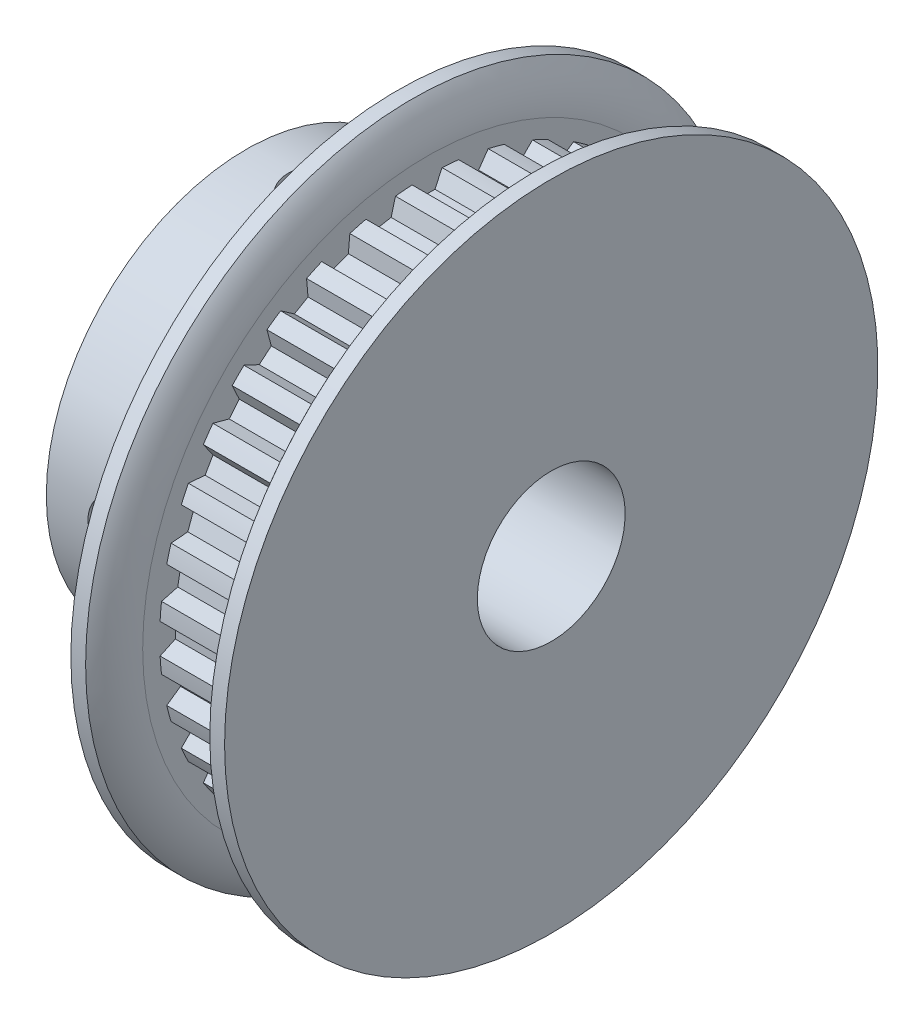
SolidWorks part; units mm, degrees
ref_plane "Front Plane" through (0, 0, 0) normal (0, 0, 1) x (1, 0, 0)
ref_plane "Top Plane" through (0, 0, 0) normal (0, 1, 0) x (1, 0, 0)
ref_plane "Right Plane" through (0, 0, 0) normal (1, 0, 0) x (0, 0, -1)
sketch "Sketch2" plane through (0, 0, 0) normal (1, 0, 0) x (0, 0, -1)
  line L3 (0, 0) -> (0, 10.8204) construction
  line L6 (0, -11.3284) -> (0, -11.6459) construction
  line L7 (-0.5715, 11.314) -> (-0.3389, 10.8151)
  line L8 (0.5715, 11.314) -> (0.3389, 10.8151)
  line L9 (-0.5715, 11.314) -> (-0.6438, 11.4691)
  line L10 (0.5715, 11.314) -> (0.6438, 11.4691)
  line L12 (-0.3389, 10.8151) -> (0.3389, 10.8151)
  line L14 (0, 11.3284) -> (0, 11.6459) construction
  line L15 (0, 0) -> (0, -1.143) construction
  circle A0 centre (0, 0) radius 11.6459 construction
  circle A1 centre (0, 0) radius 10.8204 construction
  circle A2 centre (0, 0) radius 11.3284 construction
  arc A7 (0.6438, 11.4691) -> (-0.6438, 11.4691) centre (0, 0) ccw
  point P5 (0, 11.4872)
  dimension "D3" = 0.3175
  dimension "D1" = 50
sketch "Sketch1" plane through (0, 0, 0) normal (0, 0, 1) x (1, 0, 0)
  line L0 (-6.5532, 0) -> (6.5532, 0) construction
  line L1 (-6.5532, 3.175) -> (6.5532, 3.175)
  line L2 (-6.5532, 3.175) -> (-6.5532, 8.5852)
  line L3 (-0.0508, 14.0335) -> (0.5842, 14.0335)
  line L4 (1.2192, 11.6459) -> (1.2192, 12.2174)
  line L5 (1.2192, 12.7889) -> (1.2192, 11.6459) construction
  line L6 (1.2192, 11.6459) -> (5.2832, 11.6459)
  line L7 (5.2832, 11.6459) -> (5.2832, 12.2174)
  line L8 (5.2832, 11.6459) -> (6.5532, 11.6459) construction
  line L9 (5.9182, 14.0335) -> (6.5532, 14.0335)
  line L10 (6.5532, 14.0335) -> (6.5532, 3.175)
  line L11 (5.9182, 11.6459) -> (5.9182, 14.0335) construction
  line L12 (-3.302, 8.5852) -> (-3.302, 3.175) construction
  line L13 (-0.0508, 14.0335) -> (-0.0508, 8.5852)
  line L14 (-0.0508, 8.5852) -> (-6.5532, 8.5852)
  arc A0 (5.2832, 12.2174) -> (5.9182, 14.0335) centre (8.1977, 12.2174) cw
  arc A1 (1.2192, 12.2174) -> (0.5842, 14.0335) centre (-1.6953, 12.2174) ccw
  dimension "Bore Size" = 6.35
  dimension "Overall Width" = 13.1064
  dimension "Inside Width" = 4.064
  dimension "OD" = 28.067
  dimension "D2" = 23.2918
  dimension "D3" = 1.143
  dimension "D4" = 0.5715
  dimension "Outside Width" = 6.604
revolve "Revolve1" add sketch "Sketch1" angle 360 mid plane about L0
sketch "Sketch4" plane through (1.2192, 0, 0) normal (1, 0, 0) x (0, 0, -1)
  circle A0 centre (0, 0) radius 11.4872
  circle A2 centre (0, 0) radius 11.6459
  circle A3 centre (0, 0) radius 11.6459 construction
extrude "Cut-Extrude2" cut sketch "Sketch4" along normal up to surface (4.064 mm away) up to face at (5.2832, 0, 11.6459)
sketch "Sketch3" plane through (1.2192, 0, 0) normal (1, 0, 0) x (0, 0, -1)
  line L2 (-0.5715, 11.314) -> (-0.3389, 10.8151) construction
  line L3 (-0.3389, 10.8151) -> (0.3389, 10.8151) construction
  line L4 (0.5715, 11.314) -> (0.3389, 10.8151) construction
  line L5 (-0.6438, 11.4691) -> (-0.3389, 10.8151)
  line L6 (-0.3389, 10.8151) -> (0.3389, 10.8151)
  line L7 (0.6438, 11.4691) -> (0.3389, 10.8151)
  arc A1 (0.6438, 11.4691) -> (-0.6438, 11.4691) centre (0, 0) ccw construction
  arc A2 (0.6438, 11.4691) -> (-0.6438, 11.4691) centre (0, 0) ccw
extrude "Cut-Extrude1" cut sketch "Sketch3" along normal up to surface (4.064 mm away)
pattern_circular "CirPattern1" count 36 over 360 about axis through (0, 0, 0) along (1, 0, 0) of "Cut-Extrude1"
sketch "Sketch5" plane through (0, 0, 0) normal (0, 0, 1) x (1, 0, 0)
  line L1 (5.2832, 12.2174) -> (5.2832, -12.2174) construction
  point P0 (5.2832, 0)
sketch "Sketch6" plane through (0, 0, 0) normal (0, 1, 0) x (1, 0, 0)
  line L0 (-6.5532, 0) -> (-4.7625, 0) construction
  line L1 (-6.5532, 14.0335) -> (-6.5532, -14.0335) construction
  line L2 (-0.0508, 0) -> (-1.8415, 0) construction
  line L4 (-0.0508, 14.0335) -> (-0.0508, -14.0335) construction
  circle A0 centre (-3.302, 0) radius 1.4605
  dimension "D1" = 2.921
extrude "Cut-Extrude3" cut sketch "Sketch6" along normal through all
sketch "Sketch7" plane through (0, 0, 0) normal (0, 0, 1) x (1, 0, 0)
  line L0 (-4.4704, 8.5852) -> (-3.302, 8.5852)
  line L1 (-4.7244, 8.3312) -> (-4.7244, 3.81)
  line L2 (-4.7244, 3.81) -> (-4.4704, 3.556)
  line L3 (-4.4704, 3.556) -> (-3.302, 3.556)
  line L4 (-3.302, 3.556) -> (-3.302, 8.5852) construction
  line L5 (-0.0508, 8.5852) -> (-6.5532, 8.5852) construction
  line L6 (-4.7244, 8.3312) -> (-4.4704, 8.5852)
  line L8 (-3.302, 8.5852) -> (-3.302, 3.556)
  point P0 (-4.7244, 8.5852)
  point P4 (-4.7244, 3.556)
  dimension "D1" = 2.8448
  dimension "D2" = 0.381
revolve "Revolve2" add sketch "Sketch7" angle 360 mid plane about L4
sketch "Sketch8" plane through (0, 8.5852, 0) normal (0, 1, 0) x (1, 0, 0)
  line L1 (-3.302, 0.8212) -> (-4.0132, 0.4106)
  line L2 (-4.0132, 0.4106) -> (-4.0132, -0.4106)
  line L3 (-4.0132, -0.4106) -> (-3.302, -0.8212)
  line L4 (-3.302, -0.8212) -> (-2.5908, -0.4106)
  line L5 (-2.5908, -0.4106) -> (-2.5908, 0.4106)
  line L6 (-2.5908, 0.4106) -> (-3.302, 0.8212)
  circle A0 centre (-3.302, 0) radius 0.7112 construction
  dimension "D1" = 1.4224
extrude "Cut-Extrude4" cut sketch "Sketch8" against normal blind 1.016
pattern_circular "CirPattern2" count 2 over 90 about axis through (-6.5532, 0, 0) along (-1, 0, 0) of "Cut-Extrude3"
pattern_circular "CirPattern3" count 2 over 90 about axis through (0, 0, 0) along (1, 0, 0) of bodies 107
equation "\"D3@Sketch2\" = (\"hs@Sketch2\"-\"ht@Sketch2\")/2"
equation "\"D2@Sketch1\" = \"PD@Sketch2\""
equation "\"D3@Sketch1\" = \"hs@Sketch2\""
equation "\"D4@Sketch1\" = \"D3@Sketch1\"/2"
